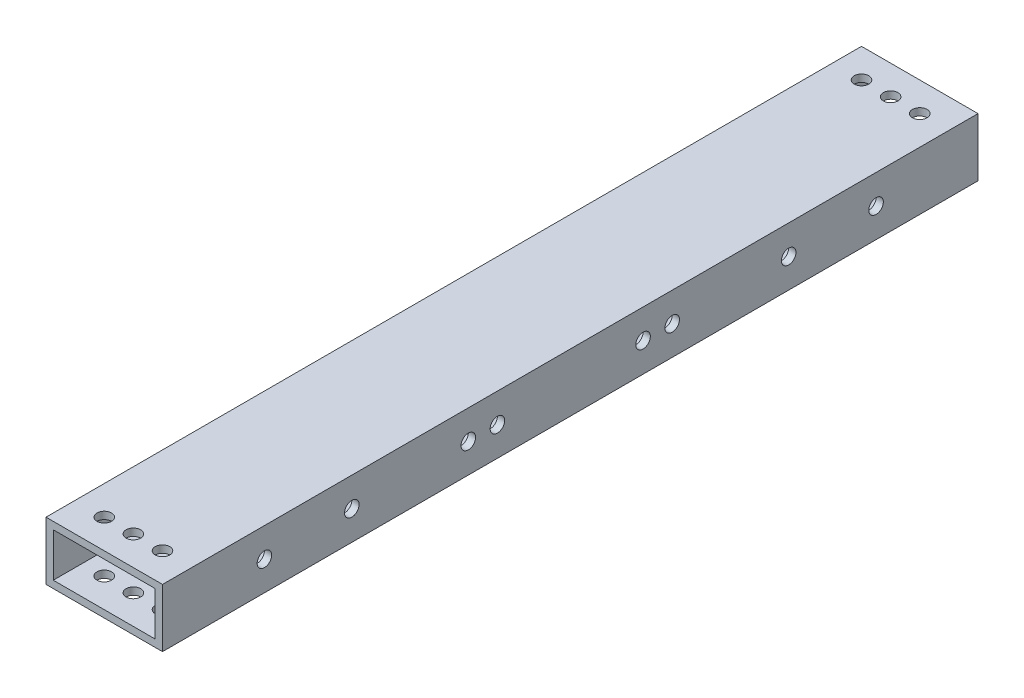
SolidWorks part; units mm, degrees
ref_plane "Front Plane" through (0, 0, 0) normal (0, 0, 1) x (1, 0, 0)
ref_plane "Top Plane" through (0, 0, 0) normal (0, 1, 0) x (1, 0, 0)
ref_plane "Right Plane" through (0, 0, 0) normal (1, 0, 0) x (0, 0, -1)
sketch "Sketch1" plane through (0, 0, 0) normal (0, 0, 1) x (1, 0, 0)
  line L0 (3.175, 22.225) -> (47.625, 22.225)
  line L1 (0, 0) -> (50.8, 0)
  line L2 (0, 0) -> (0, 25.4)
  line L3 (0, 25.4) -> (50.8, 25.4)
  line L4 (50.8, 0) -> (50.8, 25.4)
  line L5 (47.625, 3.175) -> (47.625, 22.225)
  line L6 (3.175, 3.175) -> (47.625, 3.175)
  line L7 (3.175, 3.175) -> (3.175, 22.225)
  dimension "D1" = 25.4
  dimension "D2" = 50.8
  dimension "D3" = 3.175
extrude "Boss-Extrude1" add sketch "Sketch1" along normal blind 355.6
sketch "Sketch2" plane through (0, 0, 0) normal (-1, 0, 0) x (0, 0, 1)
  line L0 (177.8, 25.4) -> (177.8, 12.7) construction
  line L1 (355.6, 25.4) -> (0, 25.4) construction
  line L2 (133.35, 12.7) -> (82.55, 12.7) construction
  line L4 (82.55, 12.7) -> (44.45, 12.7) construction
  line L5 (177.8, 12.7) -> (146.05, 12.7) construction
  line L6 (146.05, 12.7) -> (133.35, 12.7) construction
  circle A0 centre (133.35, 12.7) radius 3.175
  circle A1 centre (146.05, 12.7) radius 3.175
  circle A4 centre (82.55, 12.7) radius 3.175
  circle A5 centre (44.45, 12.7) radius 3.175
  circle A6 centre (209.55, 12.7) radius 3.175
  circle A7 centre (222.25, 12.7) radius 3.175
  circle A8 centre (273.05, 12.7) radius 3.175
  circle A9 centre (311.15, 12.7) radius 3.175
  dimension "D4" = 6.35
  dimension "D1" = 12.7
  dimension "D2" = 31.75
  dimension "D3" = 12.7
  dimension "D5" = 38.1
  dimension "D6" = 95.25
extrude "Cut-Extrude1" cut sketch "Sketch2" against normal through all both and the other way through all
hole_wizard "1/4 (0.25) Diameter Hole1" positions "Sketch3" profile "Sketch4" hole size "1/4" standard "ANSI Inch" end condition through all
sketch "Sketch3" plane through (0, 25.4, 0) normal (0, 1, 0) x (1, 0, 0)
  line L0 (12.7, -342.9) -> (25.4, -342.9)
  line L1 (25.4, -342.9) -> (38.1, -342.9)
  line L4 (25.4, -12.7) -> (12.7, -12.7)
  line L5 (12.7, -12.7) -> (12.7, -342.9)
  line L8 (0, -355.6) -> (0, 0) construction
  line L9 (25.4, -12.7) -> (38.1, -12.7)
  line L10 (50.8, 0) -> (0, 0) construction
  line L11 (50.8, -355.6) -> (0, -355.6) construction
  point P0 (12.7, -12.7)
  point P2 (25.4, -12.7)
  point P4 (38.1, -12.7)
  point P6 (12.7, -342.9)
  point P8 (25.4, -342.9)
  point P10 (38.1, -342.9)
  dimension "D2" = 12.7
  dimension "D1" = 12.7
  dimension "D3" = 12.7
  dimension "D4" = 12.7
  dimension "D5" = 12.7
  dimension "D6" = 12.7
  dimension "D7" = 12.7
sketch "Sketch4" plane through (12.7, 25.4, 12.7) normal (1, 0, 0) x (0, 0, 1)
  line L0 (0, 0) -> (0, 25.4)
  line L1 (0, 25.4) -> (3.175, 25.4)
  line L2 (3.175, 25.4) -> (3.175, 0)
  line L5 (3.175, 0) -> (0, 0)
  line L11 (0, -6.35) -> (0, 107.95) construction
  dimension "Thru Hole Dia." = 6.35
  dimension "Thru Hole Depth" = 25.4
